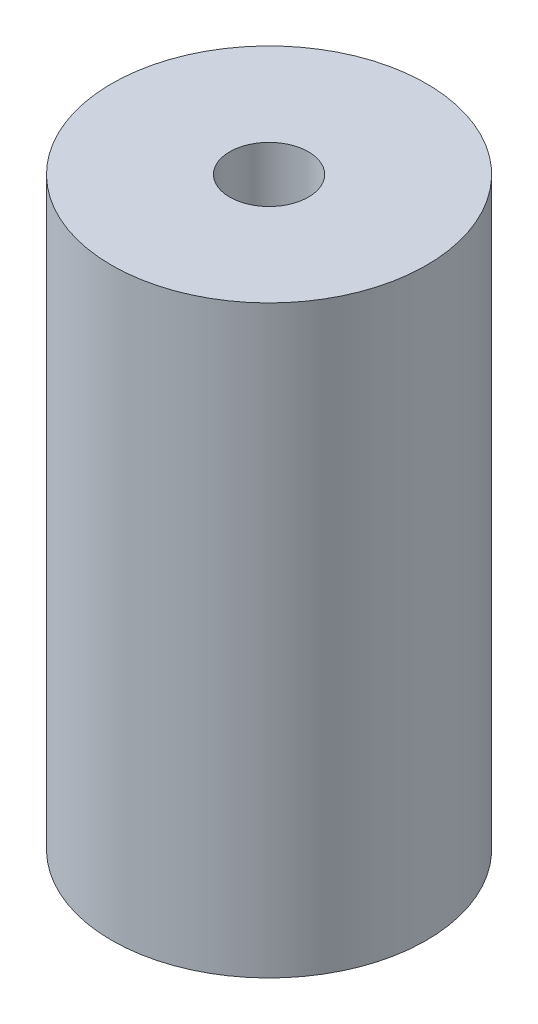
SolidWorks part; units mm, degrees
ref_plane "Front Plane" through (0, 0, 0) normal (0, 0, 1) x (1, 0, 0)
ref_plane "Top Plane" through (0, 0, 0) normal (0, 1, 0) x (1, 0, 0)
ref_plane "Right Plane" through (0, 0, 0) normal (1, 0, 0) x (0, 0, -1)
sketch "Sketch1" plane through (0, 0, 0) normal (0, 1, 0) x (1, 0, 0)
  circle A0 centre (0, 0) radius 8.89
  circle A1 centre (0, 0) radius 2.2225
  dimension "D1" = 17.78
  dimension "D2" = 4.445
extrude "Boss-Extrude1" add sketch "Sketch1" along normal blind 33.02
